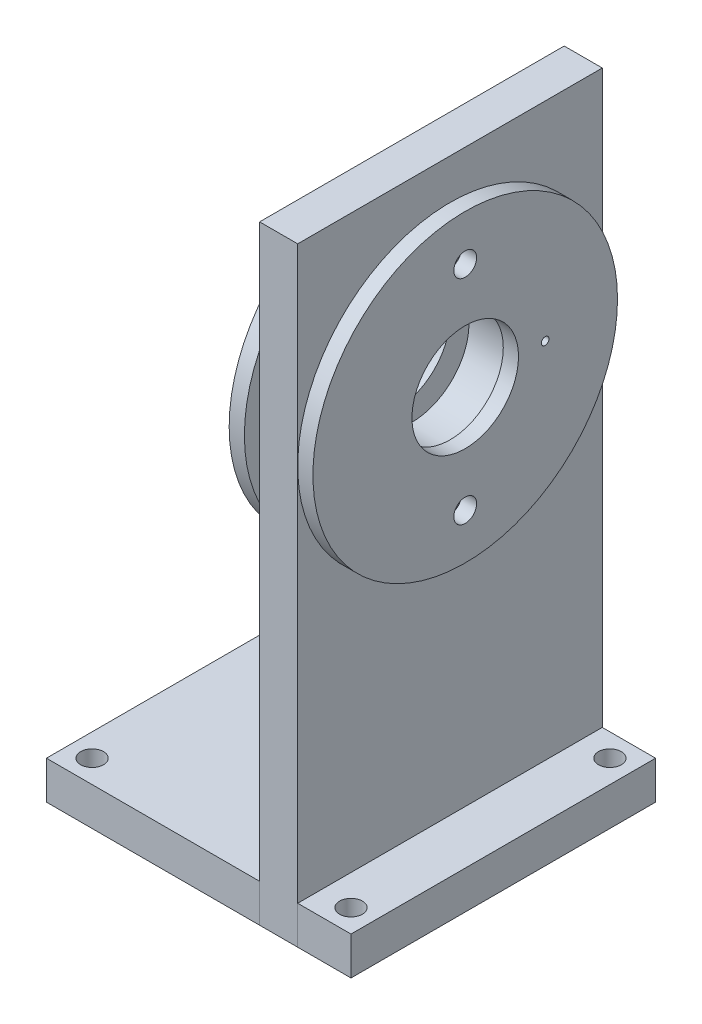
SolidWorks part; units mm, degrees
ref_plane "Front Plane" through (0, 0, 0) normal (0, 0, 1) x (1, 0, 0)
ref_plane "Top Plane" through (0, 0, 0) normal (0, 1, 0) x (1, 0, 0)
ref_plane "Right Plane" through (0, 0, 0) normal (1, 0, 0) x (0, 0, -1)
sketch "Sketch1" plane through (0, 0, 0) normal (1, 0, 0) x (0, 0, -1)
  line L1 (0, 0) -> (-20, 0)
  line L2 (-20, 0) -> (-20, 80)
  line L3 (-20, 80) -> (20, 80)
  line L4 (20, 80) -> (20, 0)
  line L5 (20, 0) -> (0, 0)
  circle A0 centre (0, 54.7) radius 7.5
  circle A1 centre (10.5, 54.7) radius 1
  dimension "D2" = 15
  dimension "D3" = 2
  dimension "D1" = 54.7
  dimension "D4" = 10.5
  dimension "D5" = 20
  dimension "D6" = 80
  dimension "D7" = 40
extrude "Boss-Extrude1" add sketch "Sketch1" along normal blind 5
sketch "Sketch2" plane through (5, 0, 0) normal (1, 0, 0) x (0, 0, -1)
  circle A0 centre (0, 54.7) radius 7
  circle A1 centre (10.5, 54.7) radius 0.5
  circle A2 centre (0, 54.7) radius 20
  circle A3 centre (0, 68.7) radius 1.5
  circle A4 centre (0, 40.7) radius 1.5
  dimension "D1" = 14
  dimension "D2" = 1
  dimension "D3" = 3
  dimension "D4" = 14
extrude "Boss-Extrude2" add sketch "Sketch2" along normal blind 2 separate body
ref_plane "Plane1" through (-2, 0, 0) normal (-1, 0, 0) x (0, 0, 1)
sketch "Sketch4" plane through (-2, 0, 0) normal (-1, 0, 0) x (0, 0, 1)
  circle A0 centre (-10.5, 54.7) radius 1
  circle A1 centre (0, 40.7) radius 1.5
  circle A2 centre (0, 40.7) radius 1.5
  circle A3 centre (0, 68.7) radius 1.5
  circle A4 centre (0, 68.7) radius 1.5
  circle A5 centre (0, 54.7) radius 20
  circle A6 centre (0, 54.7) radius 20
  circle A9 centre (0, 54.7) radius 7
  circle A10 centre (0, 54.7) radius 7
  dimension "D4" = 2
  dimension "D1" = 0
  dimension "D2" = 0
  dimension "D3" = 0
  dimension "D5" = 0
extrude "Boss-Extrude3" add sketch "Sketch4" along normal blind 2 separate body
sketch "Sketch5" plane through (0, 0, 0) normal (0, -1, 0) x (1, 0, 0)
  line L0 (0, 20) -> (0, -20)
  line L1 (0, 0) -> (-10, 0)
  point P8 (0, 0)
  point P9 (-10, 0)
  dimension "D1" = 10
sketch "Sketch6" plane through (0, 0, 0) normal (0, -1, 0) x (1, 0, 0)
  line L0 (0, 20) -> (12, 20)
  line L1 (12, 20) -> (12, -20)
  line L2 (12, -20) -> (-28, -20)
  line L3 (-28, -20) -> (-28, 20)
  line L4 (-28, 20) -> (0, 20)
  line L5 (7, -20) -> (7, 20) construction
  line L6 (0, 7) -> (0, -7)
  line L7 (0, 20) -> (0, -20) construction
  line L8 (5, 7) -> (0, 7)
  line L9 (5, -20) -> (5, 20) construction
  line L10 (0, -7) -> (5, -7)
  line L11 (5, -7) -> (5, 7)
  circle A0 centre (-25, 17) radius 1.5
  circle A1 centre (-25, -17) radius 1.5
  circle A2 centre (9, -17) radius 1.5
  circle A3 centre (9, 17) radius 1.5
  dimension "D3" = 3
  dimension "D1" = 5
  dimension "D2" = 40
  dimension "D4" = 3
  dimension "D5" = 3
  dimension "D6" = 13
  dimension "D7" = 13
extrude "Boss-Extrude4" add sketch "Sketch6" against normal blind 5 separate body
